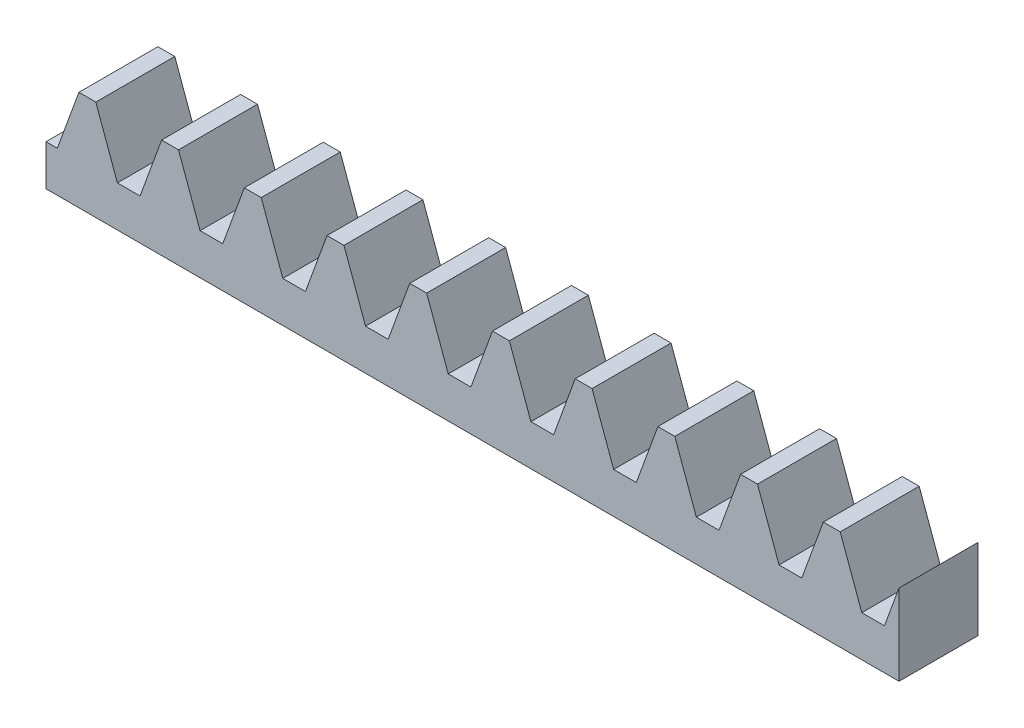
SolidWorks part; units mm, degrees
extrude "Blank" add sketch "BlankSke" against normal blind 30
sketch "BlankSke" plane through (0, 0, 0) normal (0, 0, 1) x (1, 0, 0)
  line L1 (0, 0) -> (300, 0)
  line L2 (0, 0) -> (0, 45)
  line L3 (0, 45) -> (300, 45)
  line L4 (300, 0) -> (300, 45)
  dimension "Length" = 300
  dimension "Blank_height" = 45
ref_plane "Plane1" through (0, 0, 0) normal (0, 0, 1) x (1, 0, 0)
ref_plane "Plane2" through (0, 0, 0) normal (0, 1, 0) x (1, 0, 0)
ref_plane "Plane3" through (0, 0, 0) normal (1, 0, 0) x (0, 0, -1)
other "Configuration Table"
sketch "HoldingSke" plane through (0, 0, 0) normal (0, 1, 0) x (1, 0, 0)
  line L0 (0, 0) -> (0.0278, 0.1981)
  line L1 (-15, 0) -> (100, 0) construction
  line L2 (0, 0) -> (-2.1039, 2.3779)
  line L3 (0, 0) -> (-11.863, 4.5341)
  line L4 (0, 0) -> (8.0624, 3.0949)
  line L5 (0, 0) -> (-23.7986, -8.8762)
  line L6 (0, 0) -> (-10.5278, -7.1032)
  line L9 (-71.009, 38.7566) -> (210.8988, 141.3627)
  line L10 (-76.2, 7.3779) -> (-36.2, 7.3779)
  line L11 (0, 0) -> (-30, 0)
  line L12 (-76.2, 101.6) -> (-76.033, 101.6)
  line L13 (24.9733, 27.94) -> (52.9518, 28.4284)
  line L14 (24.9733, 27.94) -> (24.9743, 27.94)
  line L15 (24.9733, 27.94) -> (100.4006, 29.5858)
  circle A0 centre (0, 0) radius 19.05
  circle A1 centre (0, 0) radius 20
  circle A2 centre (0, 0) radius 12.7
  dimension "MPH" = 40
  dimension "Diameter" = 38.1
  dimension "Num_teeth" = 21
  dimension "Pitch" = 0.2
  dimension "Show_teeth" = 998
  dimension "Thickness" = 12.7
  dimension "Ap" = 20
  dimension "Pitch_height" = 40
  dimension "Width" = 30
  dimension "Backlash" = 0.167
  dimension "Addendum_fac" = 1
  dimension "Dedendum_fac" = 1.25
  dimension "Clearance_fac" = 0.25
  dimension "Dedendum_add" = 0.001
  dimension "Length" = 300
  dimension "Module" = 5
sketch "TooCutSkeIll" plane through (0, 0, 0) normal (0, 0, 1) x (1, 0, 0)
  line L0 (-6.1999, 44.8684) -> (-2.4528, 34.5731)
  line L1 (-1.2772, 33.75) -> (1.2772, 33.75)
  line L2 (2.4528, 34.5731) -> (6.1999, 44.8684)
  line L3 (300, 45) -> (0, 45) construction
  line L4 (0, 0) -> (0, 64.897) construction
  line L5 (-13.208, 40) -> (12.954, 40) construction
  line L6 (0, 0) -> (300, 0) construction
  line L7 (4.428, 40) -> (4.428, 48.7463) construction
  line L8 (-4.428, 40) -> (-4.428, 48.7463) construction
  line L9 (6.3879, 45) -> (6.3879, 45.0254)
  line L10 (-6.3879, 45) -> (-6.3879, 45.0254)
  line L11 (-6.3879, 45.0254) -> (6.3879, 45.0254)
  arc A0 (1.2772, 33.75) -> (2.4528, 34.5731) centre (1.2772, 35.001) ccw
  arc A1 (-2.4528, 34.5731) -> (-1.2772, 33.75) centre (-1.2772, 35.001) ccw
  arc A2 (6.3879, 45) -> (6.1999, 44.8684) centre (6.3879, 44.8) ccw
  arc A3 (-6.1999, 44.8684) -> (-6.3879, 45) centre (-6.3879, 44.8) ccw
  dimension "Pitch_height" = 40
  dimension "Addendum_plus" = 5.0254
  dimension "Pressure_angle" = 20
  dimension "Gap_width" = 8.856
  dimension "Dedendum" = 6.25
extrude "ToothCutIll" [suppressed] cut sketch "TooCutSkeIll" against normal through all
sketch "TooCutSkeSim" plane through (0, 0, 0) normal (0, 0, 1) x (1, 0, 0)
  line L0 (2.1532, 33.75) -> (-2.1532, 33.75)
  line L1 (6.2571, 45.0254) -> (2.1532, 33.75)
  line L2 (0, 17.4625) -> (0, 53.467) construction
  line L3 (6.2571, 45.0254) -> (-6.2571, 45.0254)
  line L6 (-6.2571, 45.0254) -> (-2.1532, 33.75)
  line L9 (-4.428, 40) -> (4.428, 40) construction
  line L10 (0, 0) -> (300, 0) construction
  line L11 (4.428, 40) -> (4.428, 53.467) construction
  line L12 (-4.428, 40) -> (-4.428, 53.467) construction
  dimension "Pitch_height" = 40
  dimension "Addendum_plus" = 5.0254
  dimension "Pressure_angle" = 20
  dimension "Gap_width" = 8.856
  dimension "Dedendum" = 6.25
extrude "ToothCutSim" cut sketch "TooCutSkeSim" against normal through all
pattern_linear "TeethCuts" count 20 spacing 15.708 along (1, 0, 0) of "ToothCutIll", "ToothCutSim"
sketch "Sketch1" plane through (0, 0, 0) normal (0, 0, 1) x (1, 0, 0)
  line L1 (0, 0) -> (305.5316, 0)
  line L2 (0, 0) -> (0, 78.8132)
  line L3 (0, 78.8132) -> (305.5316, 78.8132)
  line L4 (305.5316, 0) -> (305.5316, 78.8132)
extrude "Cut-Extrude1" cut sketch "Sketch1" against normal blind 15
sketch "Sketch2" plane through (0, 0, 0) normal (0, -1, 0) x (1, 0, 0)
  line L1 (0, -30) -> (303.838, -30)
  line L2 (0, -30) -> (0, 18.8528)
  line L3 (0, 18.8528) -> (303.838, 18.8528)
  line L4 (303.838, -30) -> (303.838, 18.8528)
extrude "Cut-Extrude2" cut sketch "Sketch2" against normal blind 26
sketch "Sketch3" plane through (300, 0, 0) normal (1, 0, 0) x (0, 0, -1)
  line L1 (15, 45) -> (30, 45)
  line L2 (15, 45) -> (15, 26)
  line L3 (15, 26) -> (30, 26)
  line L4 (30, 45) -> (30, 26)
extrude "Cut-Extrude3" cut sketch "Sketch3" against normal blind 138
equation "' \"Module@HoldingSke\" = 6.35"
equation "' \"Num_teeth@HoldingSke\" = 12"
equation "' \"Ap@HoldingSke\" =  20"
equation "' \"Ap@HoldingSke\" = 20"
equation "' \"Width@HoldingSke\" = 0.25 * 25.4"
equation "' \"Show_teeth@HoldingSke\" = 500"
equation "' \"Backlash@HoldingSke\" = 0.009 * 25.4"
equation "' \"Addendum_fac@HoldingSke\" = 1.0"
equation "' \"Dedendum_fac@HoldingSke\" = 1.25"
equation "' \"Dedendum_add@HoldingSke\" = 0.00005 * 25.4"
equation "' \"Clearance_fac@HoldingSke\" = 0.25"
equation "' \"Pitch_height@HoldingSke\" = 1 * 25.4"
equation "' \"Length@HoldingSke\" = 4.71 * 25.4"
equation "\"Pitch@HoldingSke\" = 1 / \"Module@HoldingSke\""
equation "\"MPH@HoldingSke\" = \"Dedendum_fac@HoldingSke\" / \"Pitch@HoldingSke\" + 2 * \"Dedendum_add@HoldingSke\" + 0.002 * 25.4"
equation "\"MPH@HoldingSke\" = ((sgn( \"MPH@HoldingSke\" - \"Pitch_height@HoldingSke\")+1)*( \"MPH@HoldingSke\" - \"Pitch_height@HoldingSke\"))/2 + \"Pitch_height@HoldingSke\""
equation "\"Blank_height@BlankSke\" = \"Pitch_height@HoldingSke\" + \"Addendum_fac@HoldingSke\"  / \"Pitch@HoldingSke\" "
equation "\"Length@BlankSke\" =  \"Length@HoldingSke\""
equation "\"Face_width@Blank\" = \"Width@HoldingSke\""
equation "\"Pressure_angle@TooCutSkeIll\" = \"Ap@HoldingSke\""
equation "\"Addendum_plus@TooCutSkeIll\" =  \"Addendum_fac@HoldingSke\"  / \"Pitch@HoldingSke\" + 0.001 *25.4"
equation "\"Dedendum@TooCutSkeIll\" = \"Dedendum_fac@HoldingSke\"  / \"Pitch@HoldingSke\""
equation "\"Pitch_height@TooCutSkeIll\" =  \"MPH@HoldingSke\""
equation "\"Gap_width@TooCutSkeIll\" = 3.14159265 / 2 / \"Pitch@HoldingSke\" + 6 * \"Backlash@HoldingSke\""
equation "\"Pressure_angle@TooCutSkeSim\" = \"Ap@HoldingSke\""
equation "\"Addendum_plus@TooCutSkeSim\" =  \"Addendum_fac@HoldingSke\"  / \"Pitch@HoldingSke\" + 0.001 * 25.4"
equation "\"Dedendum@TooCutSkeSim\" = \"Dedendum_fac@HoldingSke\"  / \"Pitch@HoldingSke\""
equation "\"Pitch_height@TooCutSkeSim\" =  \"MPH@HoldingSke\""
equation "\"Gap_width@TooCutSkeSim\" = 3.14159265 / 2 / \"Pitch@HoldingSke\" + 6 * \"Backlash@HoldingSke\""
equation "\"Root_fillet@TooCutSkeIll\" = \"Clearance_fac@HoldingSke\" / \"Pitch@HoldingSke\" + \"Dedendum_add@HoldingSke\""
equation "\"Break_rad@TooCutSkeIll\" = 0.02 / \"Pitch@HoldingSke\" * 2"
equation "\"Linear_pitch@TeethCuts\" = 3.14159265 / \"Pitch@HoldingSke\""
equation "\"Num_teeth@HoldingSke\" = int( ( \"Length@HoldingSke\" + 0 ) / (3.14159265 / \"Pitch@HoldingSke\")) + 0.9999  + 1"
equation " \"Num_teeth@TeethCuts\" = int( \"Show_teeth@HoldingSke\" ) + 1"
equation " \"Num_teeth@TeethCuts\" = ((sgn( \"Num_teeth@TeethCuts\" - \"Num_teeth@HoldingSke\" )-1)*( \"Num_teeth@TeethCuts\" - \"Num_teeth@HoldingSke\" ))/-2+ \"Num_teeth@HoldingSke\""
equation " \"Num_teeth@TeethCuts\" = ((sgn( \"Num_teeth@TeethCuts\" - 2.0)+1)*( \"Num_teeth@TeethCuts\" - 2.0))/2 +2.0"
